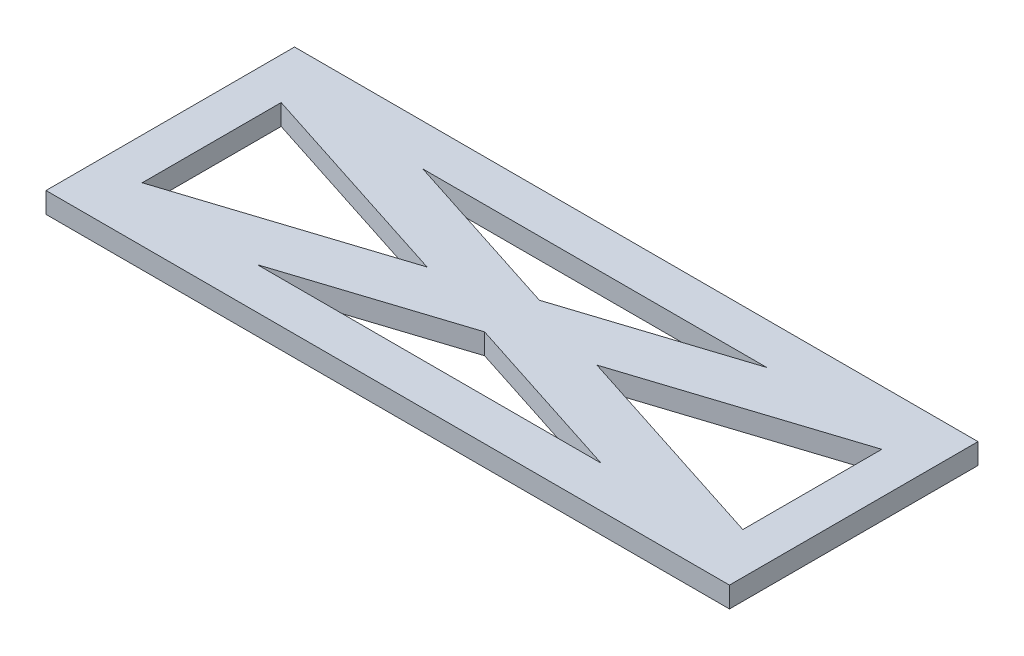
SolidWorks part; units mm, degrees
ref_plane "Front Plane" through (0, 0, 0) normal (0, 0, 1) x (1, 0, 0)
ref_plane "Top Plane" through (0, 0, 0) normal (0, 1, 0) x (1, 0, 0)
ref_plane "Right Plane" through (0, 0, 0) normal (1, 0, 0) x (0, 0, -1)
sketch "Sketch1" plane through (0, 0, 0) normal (0, 1, 0) x (1, 0, 0)
  line L5 (82.5, -30) -> (-82.5, 30) construction
  line L6 (82.5, 30) -> (-82.5, -30) construction
  line L62 (-82.5, 30) -> (-82.5, -30)
  line L63 (-82.5, -30) -> (82.5, -30)
  line L64 (82.5, -30) -> (82.5, 30)
  line L65 (82.5, 30) -> (-82.5, 30)
  line L66 (-72.5, 16.7742) -> (-20.5, 0)
  line L68 (-41.5, 20) -> (0, 6.6129)
  line L69 (0, 6.6129) -> (41.5, 20)
  line L75 (72.5, 16.7742) -> (20.5, 0)
  line L76 (-82.5, 0) -> (82.5, 0) construction
  line L77 (72.5, -16.7742) -> (20.5, 0)
  line L80 (0, -6.6129) -> (41.5, -20)
  line L81 (-41.5, -20) -> (0, -6.6129)
  line L84 (-72.5, -16.7742) -> (-20.5, 0)
  line L85 (-72.5, 16.7742) -> (-72.5, -16.7742)
  line L86 (-41.5, -20) -> (41.5, -20)
  line L87 (72.5, 16.7742) -> (72.5, -16.7742)
  line L88 (41.5, 20) -> (-41.5, 20)
  point P0 (0, 0)
  point P6 (-72.5, 16.7742)
  point P10 (-20.5, 0)
  point P16 (72.5, 16.7742)
  point P20 (0, 6.6129)
  point P21 (20.5, 0)
  point P22 (0, -6.6129)
  point P26 (-41.5, 20)
  point P27 (-72.5, -16.7742)
  point P30 (41.5, 20)
  dimension "D1" = 60
  dimension "D2" = 165
extrude "Boss-Extrude1" add sketch "Sketch1" along normal blind 5
